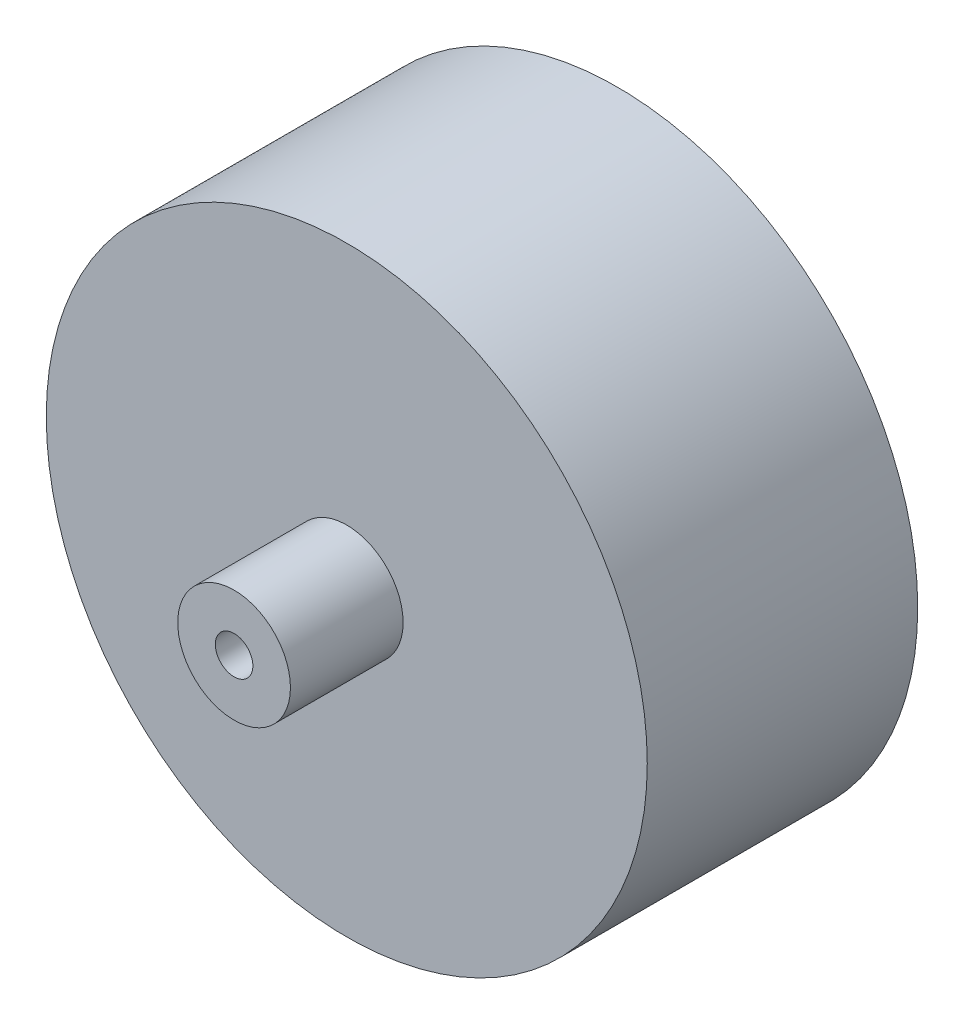
SolidWorks part; units mm, degrees
ref_plane "正面" through (0, 0, 0) normal (0, 0, 1) x (1, 0, 0)
ref_plane "平面" through (0, 0, 0) normal (0, 1, 0) x (1, 0, 0)
ref_plane "右側面" through (0, 0, 0) normal (1, 0, 0) x (0, 0, -1)
sketch "ｽｹｯﾁ1" plane through (0, 0, 0) normal (0, 0, 1) x (1, 0, 0)
  circle A0 centre (0, 0) radius 40
  dimension "D1" = 80
extrude "ﾎﾞｽ - 押し出し1" add sketch "ｽｹｯﾁ1" along normal blind 36
sketch "ｽｹｯﾁ2" plane through (0, 0, 36) normal (0, 0, 1) x (1, 0, 0)
  circle A0 centre (0, 0) radius 7.5
  dimension "D1" = 15
extrude "ﾎﾞｽ - 押し出し2" add sketch "ｽｹｯﾁ2" along normal blind 15
sketch "ｽｹｯﾁ3" plane through (0, 0, 51) normal (0, 0, 1) x (1, 0, 0)
  circle A0 centre (0, 0) radius 2.5
  dimension "D1" = 5
extrude "ｶｯﾄ - 押し出し1" cut sketch "ｽｹｯﾁ3" against normal blind 15
